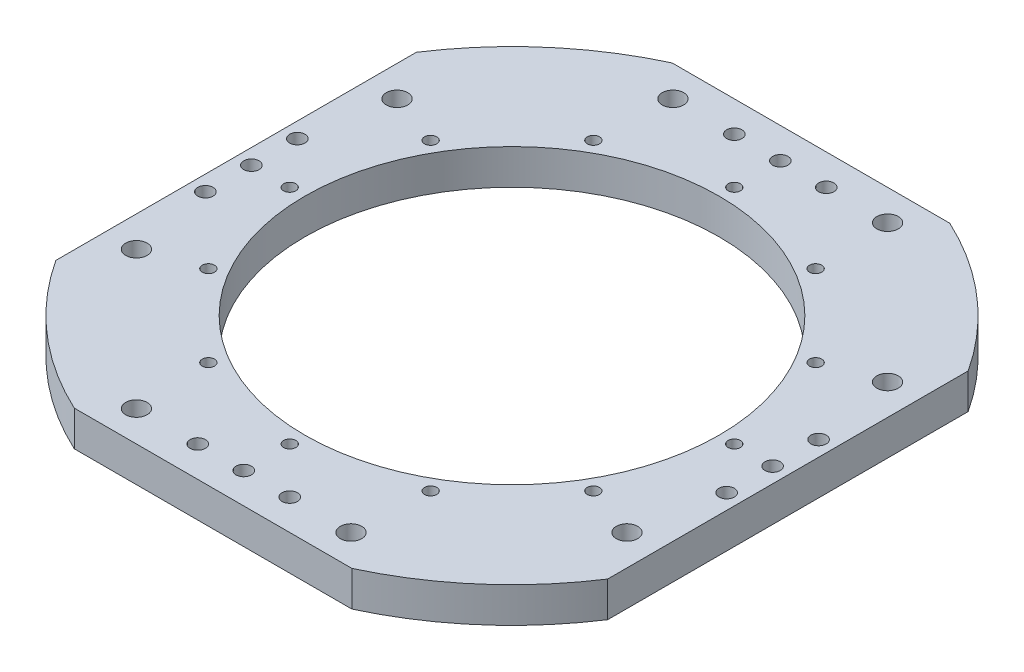
SolidWorks part; units mm, degrees
ref_plane "前视基准面" through (0, 0, 0) normal (0, 0, 1) x (1, 0, 0)
ref_plane "上视基准面" through (0, 0, 0) normal (0, 1, 0) x (1, 0, 0)
ref_plane "右视基准面" through (0, 0, 0) normal (1, 0, 0) x (0, 0, -1)
other "Configuration Table"
sketch "草图1" plane through (0, 0, 0) normal (0, 1, 0) x (1, 0, 0)
  line L0 (-180, 117.5798) -> (-180, -117.5798)
  line L1 (-180, 195) -> (180, 195) construction
  line L2 (-180, 195) -> (-180, -195) construction
  line L3 (-180, -195) -> (180, -195) construction
  line L4 (180, 195) -> (180, -195) construction
  line L5 (-180, 195) -> (180, -195) construction
  line L6 (-180, -195) -> (180, 195) construction
  line L7 (-90.5539, -195) -> (90.5539, -195)
  line L8 (180, -117.5798) -> (180, 117.5798)
  line L9 (-90.5539, 195) -> (90.5539, 195)
  arc A0 (90.5539, -195) -> (180, -117.5798) centre (0, 0) ccw
  arc A1 (-180, -117.5798) -> (-90.5539, -195) centre (0, 0) ccw
  arc A2 (-90.5539, 195) -> (-180, 117.5798) centre (0, 0) ccw
  arc A3 (180, 117.5798) -> (90.5539, 195) centre (0, 0) ccw
  circle A4 centre (0, 0) radius 135.1
  circle A5 centre (0, 0) radius 145 construction
  circle A6 centre (0, 145) radius 4
  circle A7 centre (72.5, 125.5737) radius 4
  circle A8 centre (125.5737, 72.5) radius 4
  circle A9 centre (145, 0) radius 4
  circle A10 centre (125.5737, -72.5) radius 4
  circle A11 centre (72.5, -125.5737) radius 4
  circle A12 centre (0, -145) radius 4
  circle A13 centre (-72.5, -125.5737) radius 4
  circle A14 centre (-125.5737, -72.5) radius 4
  circle A15 centre (-145, 0) radius 4
  circle A16 centre (-125.5737, 72.5) radius 4
  circle A17 centre (-72.5, 125.5737) radius 4
  point P42 (0, 0)
  dimension "D1" = 430
  dimension "D4" = 270.2
  dimension "D5" = 290
  dimension "D6" = 8
  dimension "D2" = 390
  dimension "D3" = 360
  dimension "D7" = 12
extrude "凸台-拉伸1" add sketch "草图1" along normal mid plane 23
sketch "草图2" plane through (0, 11.5, 0) normal (0, 1, 0) x (1, 0, 0)
  line L0 (0, 195) -> (0, 0) construction
  line L1 (90.5539, 195) -> (-90.5539, 195) construction
  line L2 (0, 0) -> (180, 0) construction
  line L3 (180, -117.5798) -> (180, 117.5798) construction
  circle A0 centre (0, 175) radius 5
  circle A1 centre (-30, 175) radius 5
  circle A2 centre (-70, 175) radius 7
  circle A3 centre (70, 175) radius 7
  circle A4 centre (30, 175) radius 5
  circle A5 centre (-70, -175) radius 7
  circle A6 centre (-30, -175) radius 5
  circle A7 centre (0, -175) radius 5
  circle A8 centre (30, -175) radius 5
  circle A9 centre (70, -175) radius 7
  circle A10 centre (160, 85) radius 7
  circle A11 centre (170, 30) radius 5
  circle A12 centre (170, 0) radius 5
  circle A13 centre (160, -85) radius 7
  circle A14 centre (170, -30) radius 5
  circle A15 centre (-170, -30) radius 5
  circle A16 centre (-160, -85) radius 7
  circle A17 centre (-170, 0) radius 5
  circle A18 centre (-170, 30) radius 5
  circle A19 centre (-160, 85) radius 7
  dimension "D1" = 10
  dimension "D4" = 10
  dimension "D6" = 14
  dimension "D2" = 350
  dimension "D3" = 60
  dimension "D5" = 140
  dimension "D7" = 340
  dimension "D8" = 170
  dimension "D9" = 60
  dimension "D10" = 20
extrude "切除-拉伸1" cut sketch "草图2" against normal blind 23
